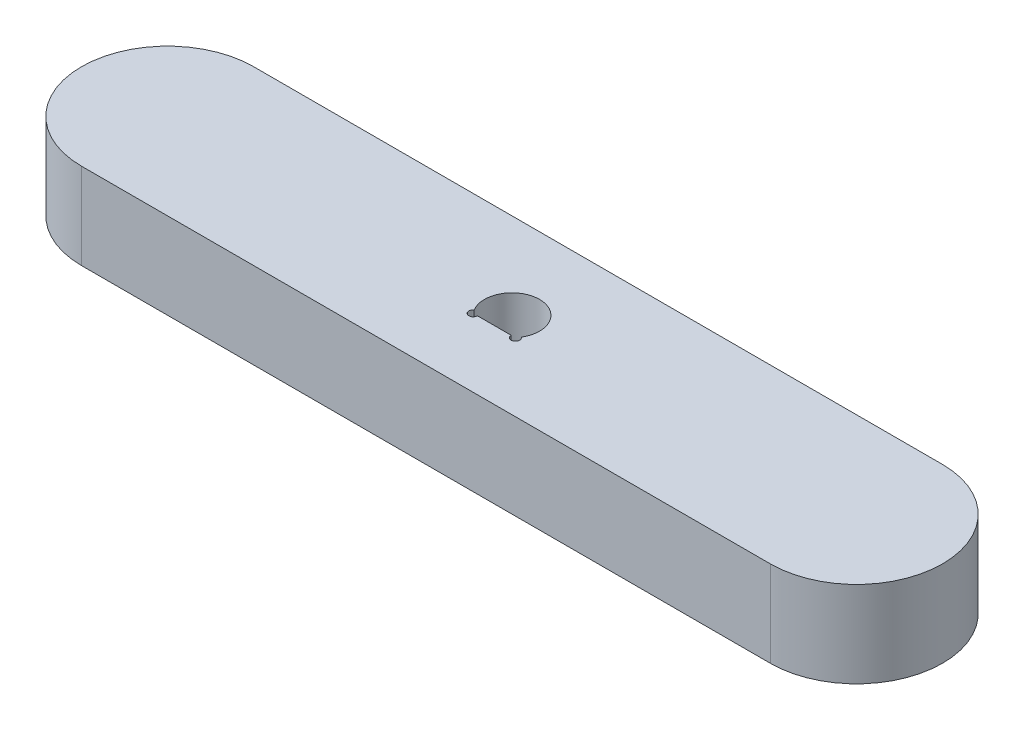
SolidWorks part; units mm, degrees
ref_plane "Front Plane" through (0, 0, 0) normal (0, 0, 1) x (1, 0, 0)
ref_plane "Top Plane" through (0, 0, 0) normal (0, 1, 0) x (1, 0, 0)
ref_plane "Right Plane" through (0, 0, 0) normal (1, 0, 0) x (0, 0, -1)
sketch "Sketch1" plane through (0, 0, 0) normal (0, 1, 0) x (1, 0, 0)
  line L0 (-40, 0) -> (0, 0) construction
  line L1 (-40, 5) -> (0, 5)
  line L2 (-40, -5) -> (0, -5)
  arc A0 (-40, 5) -> (-40, -5) centre (-40, 0) ccw
  arc A1 (0, -5) -> (0, 5) centre (0, 0) ccw
  point P3 (-20, 0)
  point P8 (-45, 0)
  point P9 (5, 0)
  dimension "D1" = 50
  dimension "D2" = 5
extrude "Boss-Extrude1" add sketch "Sketch1" along normal blind 5
sketch "Sketch2" plane through (0, 5, 0) normal (0, 1, 0) x (1, 0, 0)
  line L0 (-20, 5) -> (-20, -5) construction
  line L1 (0, 5) -> (-40, 5) construction
  line L2 (-40, -5) -> (0, -5) construction
  line L3 (-18.775, -1.0293) -> (-21.225, -1.0293)
  arc A0 (-18.775, -1.0293) -> (-21.225, -1.0293) centre (-20, 0) ccw
  circle A1 centre (-21.225, -1.0293) radius 0.25
  circle A2 centre (-18.775, -1.0293) radius 0.25
  dimension "D1" = 3.2
  dimension "D3" = 0.5
  dimension "D4" = 0.5
  dimension "D2" = 2.45
extrude "Cut-Extrude1" cut sketch "Sketch2" against normal through all both and the other way through all contours L3 A2 A0 | A0 A2 L3 | A0 L0 L3 A2 | L0 A0 A1 L3 | L3 A1 A0 | A0 A1 L3
